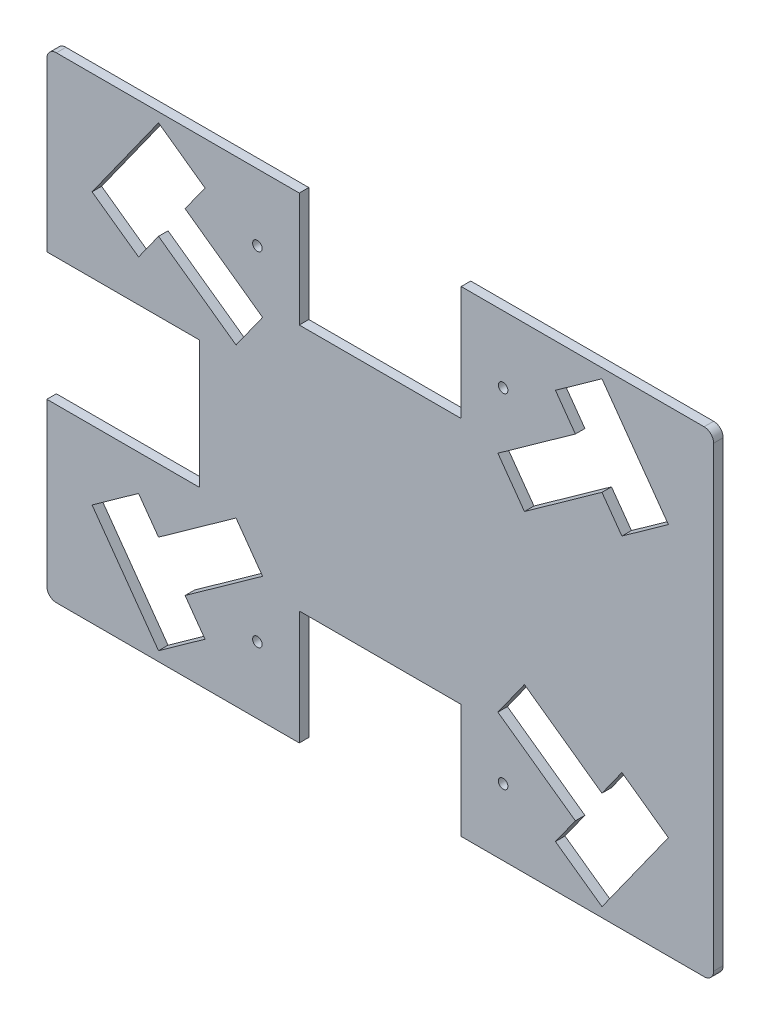
SolidWorks part; units mm, degrees
ref_plane "Plan de face" through (0, 0, 0) normal (0, 0, 1) x (1, 0, 0)
ref_plane "Plan de dessus" through (0, 0, 0) normal (0, 1, 0) x (1, 0, 0)
ref_plane "Plan de droite" through (0, 0, 0) normal (1, 0, 0) x (0, 0, -1)
sketch "Esquisse1" plane through (0, 0, 0) normal (0, 0, 1) x (1, 0, 0)
  line L0 (-175, 250) -> (175, 0) construction
  line L1 (-175, 250) -> (175, 250)
  line L2 (-175, 250) -> (-175, 0)
  line L3 (-175, 0) -> (175, 0)
  line L4 (175, 250) -> (175, 0)
  line L5 (175, 250) -> (-175, 0) construction
  point P4 (0, 0)
  dimension "D1" = 250
  dimension "D2" = 350
extrude "Boss.-Extru.1" add sketch "Esquisse1" along normal blind 5
sketch "Esquisse2" plane through (0, 0, 0) normal (0, 0, 1) x (1, 0, 0)
  line L13 (175, 250) -> (-175, 250) construction
  line L14 (0, 0) -> (0, 250) construction
  line L15 (175, 125) -> (-175, 125) construction
  line L16 (175, 0) -> (175, 250) construction
  line L17 (-175, 250) -> (-175, 0) construction
  line L71 (-175, 250) -> (0, 125) construction
  line L72 (-61.7497, 183.8537) -> (-75.6994, 164.3241)
  line L73 (-75.6994, 164.3241) -> (-116.386, 193.386)
  line L74 (-116.386, 193.386) -> (-126.8483, 178.7388)
  line L75 (-126.8483, 178.7388) -> (-151.2603, 196.176)
  line L76 (-151.2603, 196.176) -> (-116.386, 245)
  line L77 (-116.386, 245) -> (-91.974, 227.5629)
  line L78 (-91.974, 227.5629) -> (-102.4363, 212.9157)
  line L79 (-102.4363, 212.9157) -> (-61.7497, 183.8537)
  line L80 (61.7497, 183.8537) -> (75.6994, 164.3241)
  line L81 (102.4363, 212.9157) -> (61.7497, 183.8537)
  line L82 (75.6994, 164.3241) -> (116.386, 193.386)
  line L83 (126.8483, 178.7388) -> (151.2603, 196.176)
  line L84 (116.386, 193.386) -> (126.8483, 178.7388)
  line L85 (91.974, 227.5629) -> (102.4363, 212.9157)
  line L86 (116.386, 245) -> (91.974, 227.5629)
  line L87 (151.2603, 196.176) -> (116.386, 245)
  line L88 (61.7497, 66.1463) -> (75.6994, 85.6759)
  line L89 (75.6994, 85.6759) -> (116.386, 56.614)
  line L90 (102.4363, 37.0843) -> (61.7497, 66.1463)
  line L91 (116.386, 56.614) -> (126.8483, 71.2612)
  line L92 (126.8483, 71.2612) -> (151.2603, 53.824)
  line L93 (151.2603, 53.824) -> (116.386, 5)
  line L94 (91.974, 22.4371) -> (102.4363, 37.0843)
  line L95 (116.386, 5) -> (91.974, 22.4371)
  line L96 (-61.7497, 66.1463) -> (-75.6994, 85.6759)
  line L97 (-75.6994, 85.6759) -> (-116.386, 56.614)
  line L98 (-116.386, 56.614) -> (-126.8483, 71.2612)
  line L99 (-126.8483, 71.2612) -> (-151.2603, 53.824)
  line L100 (-102.4363, 37.0843) -> (-61.7497, 66.1463)
  line L101 (-91.974, 22.4371) -> (-102.4363, 37.0843)
  line L102 (-116.386, 5) -> (-91.974, 22.4371)
  line L103 (-151.2603, 53.824) -> (-116.386, 5)
  point P50 (-133.8232, 220.588)
  point P51 (-68.7245, 174.0889)
  dimension "D1" = 30
  dimension "D2" = 60
  dimension "D3" = 24
  dimension "D4" = 50
  dimension "D5" = 5
extrude "Enlèv. mat.-Extru.1" cut sketch "Esquisse2" along normal blind 5
fillet "Congé1" radius 5 4 edges at (-175, 0, 2.5) (175, 0, 2.5) (175, 250, 2.5) (-175, 250, 2.5)
sketch "Esquisse8" plane through (0, 0, 0) normal (0, 0, 1) x (1, 0, 0)
  line L0 (0, 250) -> (0, 0) construction
  line L1 (170, 250) -> (-170, 250) construction
  line L2 (175, 125) -> (-175, 125) construction
  line L3 (42.5, 250) -> (-42.5, 250)
  line L4 (42.5, 250) -> (42.5, 190)
  line L5 (42.5, 190) -> (-42.5, 190)
  line L6 (-42.5, 250) -> (-42.5, 190)
  line L7 (175, 5) -> (175, 245) construction
  line L8 (-175, 245) -> (-175, 5) construction
  line L9 (42.5, 60) -> (-42.5, 60)
  line L10 (-42.5, 0) -> (-42.5, 60)
  line L11 (42.5, 0) -> (42.5, 60)
  line L12 (42.5, 0) -> (-42.5, 0)
  point P9 (0, 250)
  dimension "D1" = 85
  dimension "D2" = 60
extrude "Enlèv. mat.-Extru.12" cut sketch "Esquisse8" along normal blind 5
sketch "Esquisse9" plane through (0, 0, 0) normal (0, 0, 1) x (1, 0, 0)
  line L0 (-175, 245) -> (-175, 5) construction
  line L2 (0, 251.5057) -> (0, 0) construction
  line L3 (-175, 125) -> (175, 125) construction
  line L4 (175, 5) -> (175, 245) construction
  line L5 (-42.5, 60) -> (-42.5, 0) construction
  line L8 (-170, 0) -> (-42.5, 0) construction
  circle A4 centre (-64.5, 35) radius 2.5
  circle A5 centre (64.5, 35) radius 2.5
  circle A6 centre (64.5, 215) radius 2.5
  circle A7 centre (-64.5, 215) radius 2.5
  dimension "D4" = 5
  dimension "D6" = 35
  dimension "D5" = 22
extrude "Enlèv. mat.-Extru.14" cut sketch "Esquisse9" along normal blind 5
sketch "Esquisse10" plane through (0, 0, 0) normal (0, 0, 1) x (1, 0, 0)
  line L0 (-175, 157) -> (-95, 157)
  line L1 (-175, 245) -> (-175, 5) construction
  line L2 (-95, 157) -> (-95, 90)
  line L3 (-95, 90) -> (-175, 90)
  line L4 (-175, 90) -> (-175, 157)
  line L5 (-170, 0) -> (-42.5, 0) construction
  dimension "D1" = 67
  dimension "D2" = 80
  dimension "D3" = 90
extrude "Enlèv. mat.-Extru.15" cut sketch "Esquisse10" along normal blind 10
